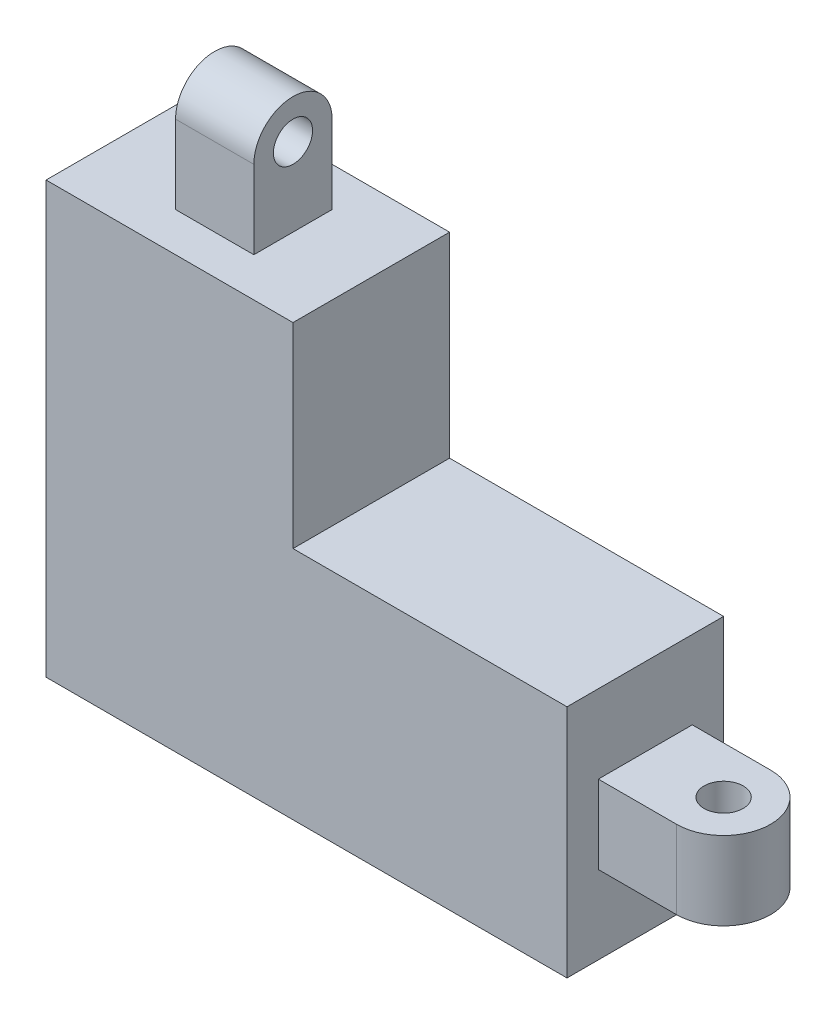
SolidWorks part; units mm, degrees
ref_plane "Front Plane" through (0, 0, 0) normal (0, 0, 1) x (1, 0, 0)
ref_plane "Top Plane" through (0, 0, 0) normal (0, 1, 0) x (1, 0, 0)
ref_plane "Right Plane" through (0, 0, 0) normal (1, 0, 0) x (0, 0, -1)
sketch "Sketch1" plane through (669.8418, 0, 0) normal (0, 0, 1) x (1, 0, 0)
  line L1 (-696.3103, 457.6379) -> (-646.3103, 457.6379)
  line L2 (-696.3103, 457.6379) -> (-696.3103, 417.6379)
  line L3 (-696.3103, 417.6379) -> (-646.3103, 417.6379)
  line L4 (-646.3103, 457.6379) -> (-646.3103, 417.6379)
  dimension "50" = 50
  dimension "D2" = 40
extrude "Boss-Extrude1" add sketch "Sketch1" along normal blind 10
sketch "Sketch5" plane through (23.5315, 0, 0) normal (1, 0, 0) x (0, 0, -1)
  line L0 (0, 417.6379) -> (0, 457.6379) construction
  line L1 (-8, 445.1379) -> (-2, 445.1379)
  line L2 (-8, 445.1379) -> (-8, 440.1379)
  line L3 (-8, 440.1379) -> (-2, 440.1379)
  line L4 (-2, 445.1379) -> (-2, 440.1379)
  line L5 (-8, 435.1379) -> (-2, 435.1379)
  line L6 (-8, 435.1379) -> (-8, 430.1379)
  line L7 (-8, 430.1379) -> (-2, 430.1379)
  line L8 (-2, 435.1379) -> (-2, 430.1379)
  line L9 (-10, 417.6379) -> (-10, 457.6379) construction
  line L10 (0, 437.6379) -> (-10, 437.6379)
  line L11 (-2, 440.1379) -> (-2, 437.6379)
  line L12 (-8, 435.1379) -> (-8, 437.6379)
  dimension "D1" = 5
  dimension "D2" = 2
  dimension "D3" = 2
  dimension "D4" = 2
  dimension "D5" = 2
  dimension "D6" = 5
  dimension "D7" = 5
extrude "Boss-Extrude3" add sketch "Sketch5" along normal blind 10 contours L4 L1 L2 L3 | L8 L5 L6 L7
sketch "Sketch6" plane through (669.8418, 445.1379, 0) normal (0, 1, 0) x (1, 0, 0)
  line L1 (-646.3103, -8) -> (-646.3103, -2) construction
  line L2 (-646.3103, -5) -> (-636.3103, -5) construction
  line L3 (-636.3103, -8) -> (-636.3103, -2) construction
  line L4 (-641.3103, -8) -> (-641.3103, -2) construction
  line L5 (-636.3103, -8) -> (-646.3103, -8) construction
  line L6 (-636.3103, -2) -> (-646.3103, -2) construction
  circle A1 centre (-641.3103, -5) radius 2
extrude "Cut-Extrude1" cut sketch "Sketch6" against normal blind 20
sketch "Sketch8" plane through (-26.4685, 0, 0) normal (-1, 0, 0) x (0, 0, 1)
  line L1 (0, 417.6379) -> (10, 417.6379)
  line L2 (0, 417.6379) -> (0, 457.6379)
  line L3 (0, 457.6379) -> (10, 457.6379)
  line L4 (10, 417.6379) -> (10, 457.6379)
extrude "Cut-Extrude2" cut sketch "Sketch8" against normal blind 25
sketch "Sketch9" plane through (0, 435.1379, 0) normal (0, 1, 0) x (1, 0, 0)
  line L1 (23.5315, -8) -> (33.5315, -8)
  line L2 (23.5315, -8) -> (23.5315, -2)
  line L3 (23.5315, -2) -> (33.5315, -2)
  line L4 (33.5315, -8) -> (33.5315, -2)
  circle A0 centre (28.5315, -5) radius 1.25
  dimension "D1" = 2.5
extrude "Boss-Extrude4" add sketch "Sketch9" along normal blind 5
sketch "Sketch10" plane through (0, 0, 8) normal (0, 0, 1) x (1, 0, 0)
  line L0 (23.5315, 417.6379) -> (23.5315, 457.6379) construction
  line L1 (33.5315, 430.1379) -> (23.5315, 430.1379)
  line L2 (33.5315, 430.1379) -> (33.5315, 435.1379)
  line L3 (33.5315, 435.1379) -> (23.5315, 435.1379)
  line L4 (23.5315, 430.1379) -> (23.5315, 435.1379)
  line L6 (33.5315, 445.1379) -> (23.5315, 445.1379)
  line L7 (33.5315, 445.1379) -> (33.5315, 440.1379)
  line L8 (33.5315, 440.1379) -> (23.5315, 440.1379)
  line L9 (23.5315, 445.1379) -> (23.5315, 440.1379)
  dimension "D1" = 5
  dimension "D2" = 5
extrude "Cut-Extrude3" cut sketch "Sketch10" against normal blind 15 contours L7 L6 L9 L8 | L2 L1 L4 L3
mirror "Mirror1" about plane through (-1.4685, 0, 0) normal (1, 0, 0) of "Boss-Extrude1"
sketch "Sketch11" plane through (0, 457.6379, 0) normal (0, 1, 0) x (1, 0, 0)
  line L0 (23.5315, 0) -> (-26.4685, 0) construction
  line L1 (-3.9685, -2.5) -> (1.0315, -2.5)
  line L2 (-3.9685, -2.5) -> (-3.9685, -7.5)
  line L3 (-3.9685, -7.5) -> (1.0315, -7.5)
  line L4 (1.0315, -2.5) -> (1.0315, -7.5)
  line L5 (23.5315, -10) -> (-26.4685, -10) construction
  line L6 (23.5315, -10) -> (23.5315, 0) construction
  line L7 (-26.4685, -10) -> (-26.4685, 0) construction
  dimension "D1" = 2.5
  dimension "D2" = 2.5
  dimension "D3" = 22.5
  dimension "D4" = 22.5
extrude "Boss-Extrude5" add sketch "Sketch11" along normal blind 10
sketch "Sketch12" plane through (1.0315, 0, 0) normal (1, 0, 0) x (0, 0, -1)
  line L0 (-5, 467.6379) -> (-5, 457.6379) construction
  line L1 (-7.5, 467.6379) -> (-2.5, 467.6379) construction
  line L2 (-7.5, 457.6379) -> (-2.5, 457.6379) construction
  line L3 (-2.5, 462.6379) -> (-7.5, 462.6379) construction
  line L4 (-2.5, 467.6379) -> (-2.5, 457.6379) construction
  line L5 (-7.5, 467.6379) -> (-7.5, 457.6379) construction
  circle A1 centre (-5, 462.6379) radius 1.25
  dimension "D1" = 2.5
extrude "Cut-Extrude4" cut sketch "Sketch12" against normal blind 10
sketch "Sketch13" plane through (1.0315, 0, 0) normal (1, 0, 0) x (0, 0, -1)
  line L0 (-7.5, 462.6379) -> (-7.5, 467.6379)
  line L1 (-7.5, 467.6379) -> (-2.5, 467.6379)
  line L2 (-2.5, 467.6379) -> (-2.5, 457.6379) construction
  line L3 (-7.5, 467.6379) -> (-2.5, 467.6379) construction
  line L4 (-2.5, 467.6379) -> (-2.5, 462.6379)
  circle A0 centre (-5, 462.6379) radius 2.5
  line M3 (-2.5, 457.6379) -> (-2.5, 467.6379)
  line M4 (-2.5, 467.6379) -> (-7.5, 467.6379)
  line M5 (-7.5, 467.6379) -> (-7.5, 457.6379)
extrude "Cut-Extrude5" cut sketch "Sketch13" against normal blind 10 contours A0 M3 M4 M5
sketch "Sketch14" plane through (0, 440.1379, 0) normal (0, 1, 0) x (1, 0, 0)
  line L0 (28.5315, -2) -> (33.5315, -2)
  line L1 (28.5315, -8) -> (33.5315, -8)
  circle A0 centre (28.5315, -5) radius 3
  line M6 (23.5315, -8) -> (33.5315, -8)
  line M7 (33.5315, -8) -> (33.5315, -2)
  line M8 (33.5315, -2) -> (23.5315, -2)
extrude "Cut-Extrude6" cut sketch "Sketch14" against normal blind 10 contours A0 M6 M7 M8
scale "Scale1" bodies to scale 118 scale about centroid uniform scaling yes scale factor 2
sketch "Sketch15" plane through (0, 0, 15) normal (0, 0, 1) x (1, 0, 0)
  line L0 (48.2563, 397.467) -> (48.2563, 477.467) construction
  line L1 (-51.7437, 397.467) -> (48.2563, 397.467)
  line L2 (-51.7437, 397.467) -> (-51.7437, 422.467)
  line L3 (-51.7437, 422.467) -> (48.2563, 422.467)
  line L4 (48.2563, 397.467) -> (48.2563, 422.467)
  line L5 (58.2563, 432.467) -> (48.2563, 432.467) construction
  line L6 (48.2563, 477.467) -> (-51.7437, 477.467) construction
  line L7 (-51.7437, 422.467) -> (-18.2788, 422.467)
  line L8 (-51.7437, 422.467) -> (-51.7437, 477.467)
  line L9 (-51.7437, 477.467) -> (-18.2788, 477.467)
  line L10 (-18.2788, 422.467) -> (-18.2788, 477.467)
  line L11 (3.2563, 487.467) -> (3.2563, 477.467) construction
  line L12 (48.2563, 477.467) -> (13.2563, 477.467)
  line L13 (48.2563, 477.467) -> (48.2563, 452.467)
  line L14 (48.2563, 452.467) -> (13.2563, 452.467)
  line L15 (13.2563, 477.467) -> (13.2563, 452.467)
  line L16 (58.2563, 442.467) -> (48.2563, 442.467) construction
  line M4 (48.2563, 477.467) -> (-51.7437, 477.467)
  line M5 (-51.7437, 477.467) -> (-51.7437, 397.467)
  line M6 (-51.7437, 397.467) -> (48.2563, 397.467)
  line M7 (48.2563, 397.467) -> (48.2563, 477.467)
  dimension "D1" = 10
  dimension "D2" = 10
  dimension "D3" = 10
extrude "Cut-Extrude7" cut sketch "Sketch15" against normal blind 30 contours L3 L10 M4 M5 | L3 M5 M6 M7 | L15 L14 M4 M7
